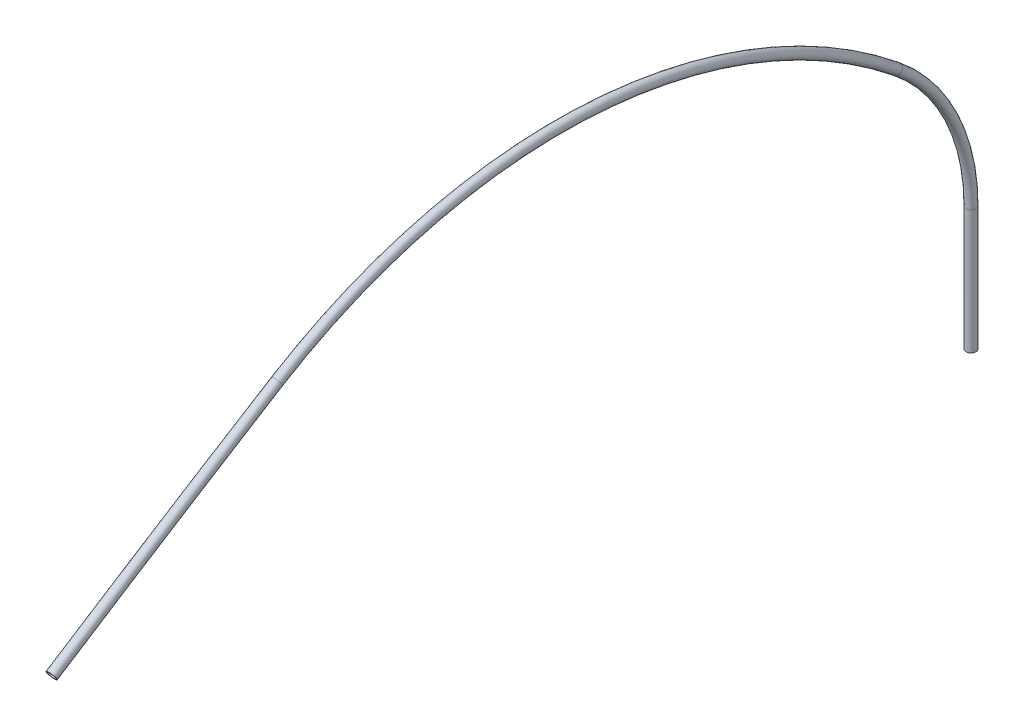
SolidWorks part; units mm, degrees
ref_plane "Alzado" through (0, 0, 0) normal (0, 0, 1) x (1, 0, 0)
ref_plane "Planta" through (0, 0, 0) normal (0, 1, 0) x (1, 0, 0)
ref_plane "Vista lateral" through (0, 0, 0) normal (1, 0, 0) x (0, 0, -1)
sketch "Croquis5" plane through (0, 0, 0) normal (1, 0, 0) x (0, 0, -1)
  line L0 (-12, 40) -> (-12, 165.366)
  arc A0 (-12, 165.366) -> (-87.367, 322.9045) centre (-214.3336, 165.366) ccw
  arc A1 (-87.367, 322.9045) -> (-713.816, 362.4396) centre (-428.5562, -100.4384) ccw
  arc A2 (-713.816, 362.4396) -> (-941.7239, 218.7723) centre (6245.9153, -10930.7985) ccw
  dimension "D1" = 40
ref_plane "Plano1" through (0, 40, 12) normal (0, 1, 0) x (-1, 0, 0)
sketch "Croquis7" plane through (0, 40, 12) normal (0, 1, 0) x (-1, 0, 0)
  circle A0 centre (0, 0) radius 5
  dimension "D1" = 10
sweep "Barrer1" add profiles "Croquis7" path "Croquis5"
shell "Vaciado2" thickness 1
